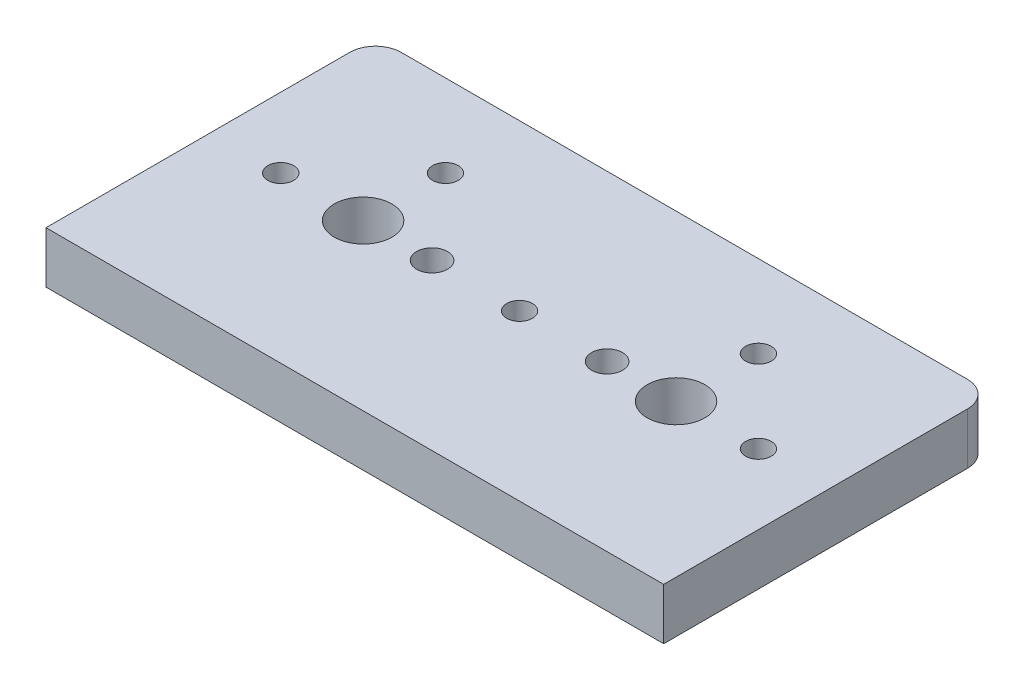
SolidWorks part; units mm, degrees
ref_plane "前视基准面" through (0, 0, 0) normal (0, 0, 1) x (1, 0, 0)
ref_plane "上视基准面" through (0, 0, 0) normal (0, 1, 0) x (1, 0, 0)
ref_plane "右视基准面" through (0, 0, 0) normal (1, 0, 0) x (0, 0, -1)
other "Configuration Table"
sketch "草图1" plane through (0, 0, 0) normal (0, 1, 0) x (1, 0, 0)
  line L0 (0, 16) -> (0, -16) construction
  line L1 (-30, 16) -> (30, 16)
  line L2 (-30, 16) -> (-30, -16)
  line L3 (-30, -16) -> (30, -16)
  line L4 (30, 16) -> (30, -16)
  line L5 (-30, 0) -> (30, 0) construction
  circle A1 centre (15.2, 0) radius 4.1
  circle A2 centre (-15.2, 0) radius 4.1
  circle A3 centre (15.2, 0) radius 2.9
  circle A4 centre (-15.2, 0) radius 2.9
  dimension "D3" = 15.2
  dimension "D4" = 8.2
  dimension "D5" = 5.8
  dimension "D1" = 60
  dimension "D2" = 32
extrude "凸台-拉伸1" add sketch "草图1" along normal blind 5 contours L2 L1 L4 L3
sketch "草图2" plane through (0, 5, 0) normal (0, 1, 0) x (1, 0, 0)
  line L0 (0, 16) -> (0, -16) construction
  line L1 (-30, 16) -> (30, 16) construction
  line L2 (-30, -16) -> (30, -16) construction
  line L3 (30, 16) -> (30, -16) construction
  circle A0 centre (8.5, 0) radius 1.5
  circle A1 centre (-8.5, 0) radius 1.5
  circle A2 centre (0, 0) radius 1.25
  circle A3 centre (15.2, 0) radius 4.1
  circle A4 centre (15.2, 0) radius 2.8
  circle A5 centre (-15.2, 0) radius 4.1
  circle A6 centre (-15.2, 0) radius 2.8
  circle A7 centre (15.2, 8) radius 1.25
  circle A8 centre (23.2, 0) radius 1.25
  circle A9 centre (-23.2, 0) radius 1.25
  circle A10 centre (-15.2, 8) radius 1.25
  point P12 (30, 0)
  point P26 (0, 0)
  point P27 (0, 0)
  point P28 (0, 0)
  dimension "D1" = 3
  dimension "D3" = 2.5
  dimension "D4" = 5.6
  dimension "D5" = 8.2
  dimension "D7" = 2.5
  dimension "D8" = 2.5
  dimension "D2" = 17
  dimension "D6" = 15.2
  dimension "D9" = 8
  dimension "D10" = 8
extrude "切除-拉伸1" cut sketch "草图2" along direction (0, -1, 0) on the side against the normal up to surface (5 mm away) contours A1 | A0 | A2 | A10 | A9 | A7 | A8 | A6 | A4
fillet "圆角1" radius 2.5 2 edges at (-30, 2.5, -16) (30, 2.5, -16)
